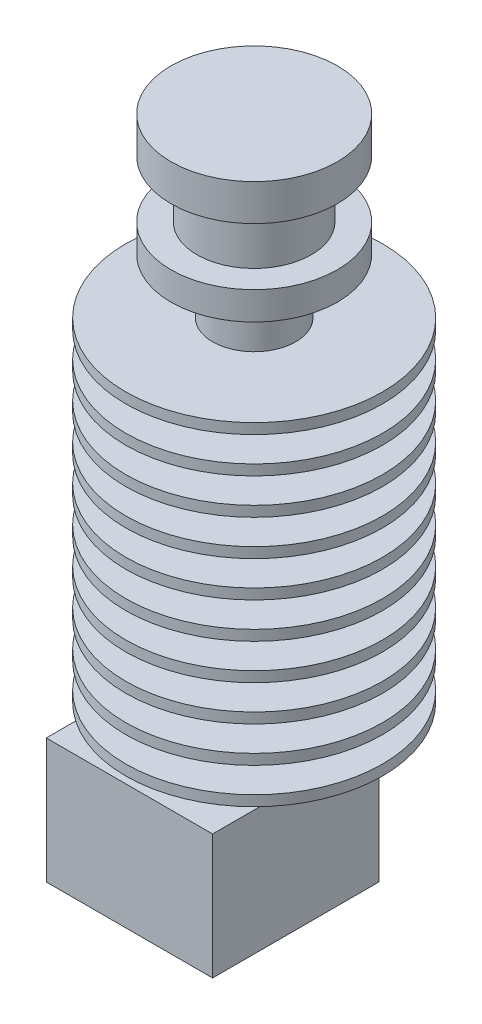
SolidWorks part; units mm, degrees
material "Liga 1060"
ref_plane "Plano frontal" through (0, 0, 0) normal (0, 0, 1) x (1, 0, 0)
ref_plane "Plano superior" through (0, 0, 0) normal (0, 1, 0) x (1, 0, 0)
ref_plane "Plano direito" through (0, 0, 0) normal (1, 0, 0) x (0, 0, -1)
sketch "Esboço1" plane through (0, 0, 0) normal (0, 0, 1) x (1, 0, 0)
  line L0 (0, 51.6592) -> (0, 1.6592)
  line L1 (0, 51.6592) -> (8, 51.6592)
  line L2 (8, 51.6592) -> (8, 48.1592)
  line L3 (5.5, 48.1592) -> (5.5, 42.6592)
  line L4 (5.5, 42.6592) -> (8, 42.6592)
  line L5 (8, 42.6592) -> (8, 39.9592)
  line L6 (8, 39.9592) -> (4, 39.9592)
  line L7 (5.5, 48.1592) -> (8, 48.1592)
  line L8 (4, 39.9592) -> (4, 34.6592)
  line L9 (4, 34.6592) -> (12.35, 34.6592)
  line L10 (12.35, 34.6592) -> (12.35, 33.6592)
  line L11 (12.35, 2.6592) -> (2, 2.6592)
  line L12 (2, 2.6592) -> (0, 2.6592) construction
  line L13 (2, 2.6592) -> (2, 1.6592)
  line L14 (2, 1.6592) -> (0, 1.6592)
  line L15 (0, 51.6592) -> (0, 1.6592) construction
  line L16 (12.35, 33.6592) -> (4, 33.6592)
  line L17 (4, 33.6592) -> (4, 31.2148)
  line L18 (4, 31.2148) -> (12.35, 31.2148)
  line L19 (12.35, 31.2148) -> (12.35, 30.2148)
  line L20 (12.35, 30.2148) -> (4, 30.2148)
  line L21 (4, 30.2148) -> (4, 27.7703)
  line L22 (4, 27.7703) -> (12.35, 27.7703)
  line L23 (12.35, 27.7703) -> (12.35, 26.7703)
  line L24 (12.35, 26.7703) -> (4, 26.7703)
  line L25 (4, 26.7703) -> (4, 24.3259)
  line L26 (4, 24.3259) -> (12.35, 24.3259)
  line L27 (12.35, 24.3259) -> (12.35, 23.3259)
  line L28 (12.35, 23.3259) -> (4, 23.3259)
  line L29 (4, 23.3259) -> (4, 20.8815)
  line L30 (4, 20.8815) -> (12.35, 20.8815)
  line L31 (12.35, 20.8815) -> (12.35, 19.8815)
  line L32 (12.35, 19.8815) -> (4, 19.8815)
  line L33 (4, 19.8815) -> (4, 17.437)
  line L34 (4, 17.437) -> (12.35, 17.437)
  line L35 (12.35, 17.437) -> (12.35, 16.437)
  line L36 (12.35, 16.437) -> (4, 16.437)
  line L37 (4, 16.437) -> (4, 13.9926)
  line L38 (4, 13.9926) -> (12.35, 13.9926)
  line L39 (12.35, 13.9926) -> (12.35, 12.9926)
  line L40 (12.35, 12.9926) -> (4, 12.9926)
  line L41 (4, 12.9926) -> (4, 10.5481)
  line L42 (4, 10.5481) -> (12.35, 10.5481)
  line L43 (12.35, 10.5481) -> (12.35, 9.5481)
  line L44 (12.35, 9.5481) -> (4, 9.5481)
  line L45 (4, 9.5481) -> (4, 7.1037)
  line L46 (4, 7.1037) -> (12.35, 7.1037)
  line L47 (12.35, 7.1037) -> (12.35, 6.1037)
  line L48 (12.35, 6.1037) -> (4, 6.1037)
  line L49 (4, 6.1037) -> (4, 3.6592)
  line L50 (4, 3.6592) -> (12.35, 3.6592)
  line L51 (12.35, 3.6592) -> (12.35, 2.6592)
  line L55 (4, 2.6592) -> (4, 0.2148) [skipped]
  line L56 (4, 0.2148) -> (12.35, 0.2148) [skipped]
  line L57 (12.35, 2.6592) -> (4, 2.6592) [skipped]
  dimension "D1" = 32
  dimension "D2" = 3.5
  dimension "D3" = 5.5
  dimension "D4" = 2.7
  dimension "D5" = 1
  dimension "D6" = 50
  dimension "D7" = 4
  dimension "D8" = 24.7
  dimension "D9" = 1
  dimension "D11" = 1
  dimension "D10" = 10
revolve "Revolução1" add sketch "Esboço1" angle 360 about L15
sketch "Esboço3" plane through (0, 1.6592, 0) normal (0, -1, 0) x (1, 0, 0)
  line L0 (0, 0) -> (0, 4) construction
  line L2 (-8, 12) -> (8, 12)
  line L3 (-8, 12) -> (-8, -4)
  line L4 (-8, -4) -> (8, -4)
  line L5 (8, 12) -> (8, -4)
  line L6 (-8, 12) -> (8, -4) construction
  line L7 (-8, -4) -> (8, 12) construction
extrude "Ressalto-extrusão1" add sketch "Esboço3" along normal blind 12
sketch "Esboço4" plane through (0, -10.3408, 0) normal (0, -1, 0) x (1, 0, 0)
  circle A0 centre (0, 0) radius 3
extrude "Ressalto-extrusão2" add sketch "Esboço4" along normal blind 5 draft 26
sketch "Esboço5" plane through (0, -15.3408, 0) normal (0, -1, 0) x (1, 0, 0)
  point P0 (0, 0)
